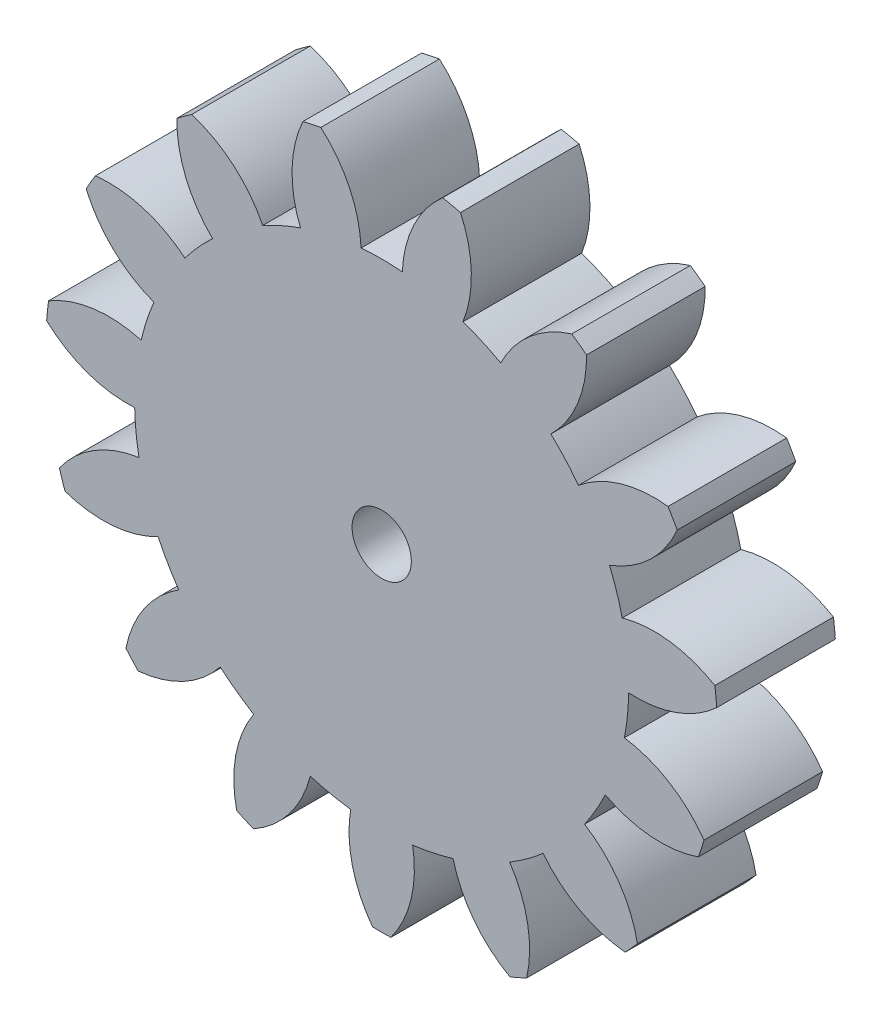
SolidWorks part; units mm, degrees
ref_plane "Płaszczyzna przednia" through (0, 0, 0) normal (0, 0, 1) x (1, 0, 0)
ref_plane "Płaszczyzna górna" through (0, 0, 0) normal (0, 1, 0) x (1, 0, 0)
ref_plane "Płaszczyzna prawa" through (0, 0, 0) normal (1, 0, 0) x (0, 0, -1)
sketch "Szkic1" plane through (0, 0, 0) normal (0, 0, 1) x (1, 0, 0)
  arc A120 (-33.8981, 2.6304) -> (-24.9935, -0.5255) centre (-25.7608, 11.45) ccw
  arc A121 (-24.9935, -0.5255) -> (-24.5566, -4.6824) centre (0, 0) ccw
  arc A122 (-24.5566, -4.6824) -> (-32.6104, -9.6208) centre (-22.8173, -16.5557) ccw
  arc A123 (-32.6104, -9.6208) -> (-32.0373, -11.3846) centre (0, 0) ccw
  arc A124 (-32.0373, -11.3846) -> (-22.6189, -10.6458) centre (-28.1908, -0.0178) ccw
  arc A125 (-22.6189, -10.6458) -> (-20.529, -14.2657) centre (0, 0) ccw
  arc A126 (-20.529, -14.2657) -> (-25.878, -22.0529) centre (-14.1108, -24.405) ccw
  arc A127 (-25.878, -22.0529) -> (-24.637, -23.4311) centre (0, 0) ccw
  arc A128 (-24.637, -23.4311) -> (-16.3334, -18.9254) centre (-25.7463, -11.4825) ccw
  arc A129 (-16.3334, -18.9254) -> (-12.9518, -21.3822) centre (0, 0) ccw
  arc A130 (-12.9518, -21.3822) -> (-14.671, -30.6718) centre (-2.9644, -28.0345) ccw
  arc A131 (-14.671, -30.6718) -> (-12.9768, -31.4262) centre (0, 0) ccw
  arc A132 (-12.9768, -31.4262) -> (-7.2237, -23.9326) centre (-18.8501, -20.9617) ccw
  arc A133 (-7.2237, -23.9326) -> (-3.1351, -24.8016) centre (0, 0) ccw
  arc A134 (-3.1351, -24.8016) -> (-0.9273, -33.9874) centre (8.6945, -26.8165) ccw
  arc A135 (-0.9273, -33.9874) -> (0.9273, -33.9874) centre (0, 0) ccw
  arc A136 (0.9273, -33.9874) -> (3.1351, -24.8016) centre (-8.6945, -26.8165) ccw
  arc A137 (3.1351, -24.8016) -> (7.2237, -23.9326) centre (0, 0) ccw
  arc A138 (7.2237, -23.9326) -> (12.9768, -31.4262) centre (18.8501, -20.9617) ccw
  arc A139 (12.9768, -31.4262) -> (14.671, -30.6718) centre (0, 0) ccw
  arc A140 (14.671, -30.6718) -> (12.9518, -21.3822) centre (2.9644, -28.0345) ccw
  arc A141 (12.9518, -21.3822) -> (16.3334, -18.9254) centre (0, 0) ccw
  arc A142 (16.3334, -18.9254) -> (24.637, -23.4311) centre (25.7463, -11.4825) ccw
  arc A143 (24.637, -23.4311) -> (25.878, -22.0529) centre (0, 0) ccw
  arc A144 (25.878, -22.0529) -> (20.529, -14.2657) centre (14.1108, -24.405) ccw
  arc A145 (20.529, -14.2657) -> (22.6189, -10.6458) centre (0, 0) ccw
  arc A146 (22.6189, -10.6458) -> (32.0373, -11.3846) centre (28.1908, -0.0178) ccw
  arc A147 (32.0373, -11.3846) -> (32.6104, -9.6208) centre (0, 0) ccw
  arc A148 (32.6104, -9.6208) -> (24.5566, -4.6824) centre (22.8173, -16.5557) ccw
  arc A149 (24.5566, -4.6824) -> (24.9935, -0.5255) centre (0, 0) ccw
  arc A150 (24.9935, -0.5255) -> (33.8981, 2.6304) centre (25.7608, 11.45) ccw
  arc A151 (33.8981, 2.6304) -> (33.7042, 4.4749) centre (0, 0) ccw
  arc A152 (33.7042, 4.4749) -> (24.3381, 5.7104) centre (27.5784, -5.8438) ccw
  arc A153 (24.3381, 5.7104) -> (23.0464, 9.6857) centre (0, 0) ccw
  arc A154 (23.0464, 9.6857) -> (29.8976, 16.1906) centre (18.8765, 20.9379) ccw
  arc A155 (29.8976, 16.1906) -> (28.9703, 17.7967) centre (0, 0) ccw
  arc A156 (28.9703, 17.7967) -> (19.9113, 15.1159) centre (27.571, 5.8786) ccw
  arc A157 (19.9113, 15.1159) -> (17.1144, 18.2222) centre (0, 0) ccw
  arc A158 (17.1144, 18.2222) -> (20.7275, 26.9513) centre (8.7283, 26.8055) ccw
  arc A159 (20.7275, 26.9513) -> (19.2271, 28.0414) centre (0, 0) ccw
  arc A160 (19.2271, 28.0414) -> (12.0417, 21.9077) centre (22.7964, 16.5845) ccw
  arc A161 (12.0417, 21.9077) -> (8.2232, 23.6078) centre (0, 0) ccw
  arc A162 (8.2232, 23.6078) -> (7.9734, 33.0519) centre (-2.929, 28.0382) ccw
  arc A163 (7.9734, 33.0519) -> (6.1593, 33.4374) centre (0, 0) ccw
  arc A164 (6.1593, 33.4374) -> (2.0899, 24.9115) centre (14.08, 24.4228) ccw
  arc A165 (2.0899, 24.9115) -> (-2.0899, 24.9115) centre (0, 0) ccw
  arc A166 (-2.0899, 24.9115) -> (-6.1593, 33.4374) centre (-14.08, 24.4228) ccw
  arc A167 (-6.1593, 33.4374) -> (-7.9734, 33.0519) centre (0, 0) ccw
  arc A168 (-7.9734, 33.0519) -> (-8.2232, 23.6078) centre (2.929, 28.0382) ccw
  arc A169 (-8.2232, 23.6078) -> (-12.0417, 21.9077) centre (0, 0) ccw
  arc A170 (-12.0417, 21.9077) -> (-19.2271, 28.0414) centre (-22.7964, 16.5845) ccw
  arc A171 (-19.2271, 28.0414) -> (-20.7275, 26.9513) centre (0, 0) ccw
  arc A172 (-20.7275, 26.9513) -> (-17.1144, 18.2222) centre (-8.7283, 26.8055) ccw
  arc A173 (-17.1144, 18.2222) -> (-19.9113, 15.1159) centre (0, 0) ccw
  arc A174 (-19.9113, 15.1159) -> (-28.9703, 17.7967) centre (-27.571, 5.8786) ccw
  arc A175 (-28.9703, 17.7967) -> (-29.8976, 16.1906) centre (0, 0) ccw
  arc A176 (-29.8976, 16.1906) -> (-23.0464, 9.6857) centre (-18.8765, 20.9379) ccw
  arc A177 (-23.0464, 9.6857) -> (-24.3381, 5.7104) centre (0, 0) ccw
  arc A178 (-24.3381, 5.7104) -> (-33.7042, 4.4749) centre (-27.5784, -5.8438) ccw
  arc A179 (-33.7042, 4.4749) -> (-33.8981, 2.6304) centre (0, 0) ccw
extrude "Dodanie-wyciągnięcie1" add sketch "Szkic1" along normal blind 12
sketch "Szkic2" plane through (0, 0, 12) normal (0, 0, 1) x (1, 0, 0)
  point P0 (0, 0)
hole_wizard "Otwór Ø6.0 (6)1" positions "Szkic2" profile "Szkic3" hole size "Ø6.0" standard "DIN" end condition up to next
sketch "Szkic3" plane through (0, 0, 12) normal (1, 0, 0) x (0, -1, 0)
  line L0 (0, 0) -> (0, 12)
  line L1 (0, 12) -> (3, 12)
  line L2 (3, 12) -> (3, 0)
  line L5 (3, 0) -> (0, 0)
  line L11 (0, -6.35) -> (0, 107.95) construction
  dimension "Średnica otworu na wylot" = 6
  dimension "Głębokość otworu na wylot" = 12
